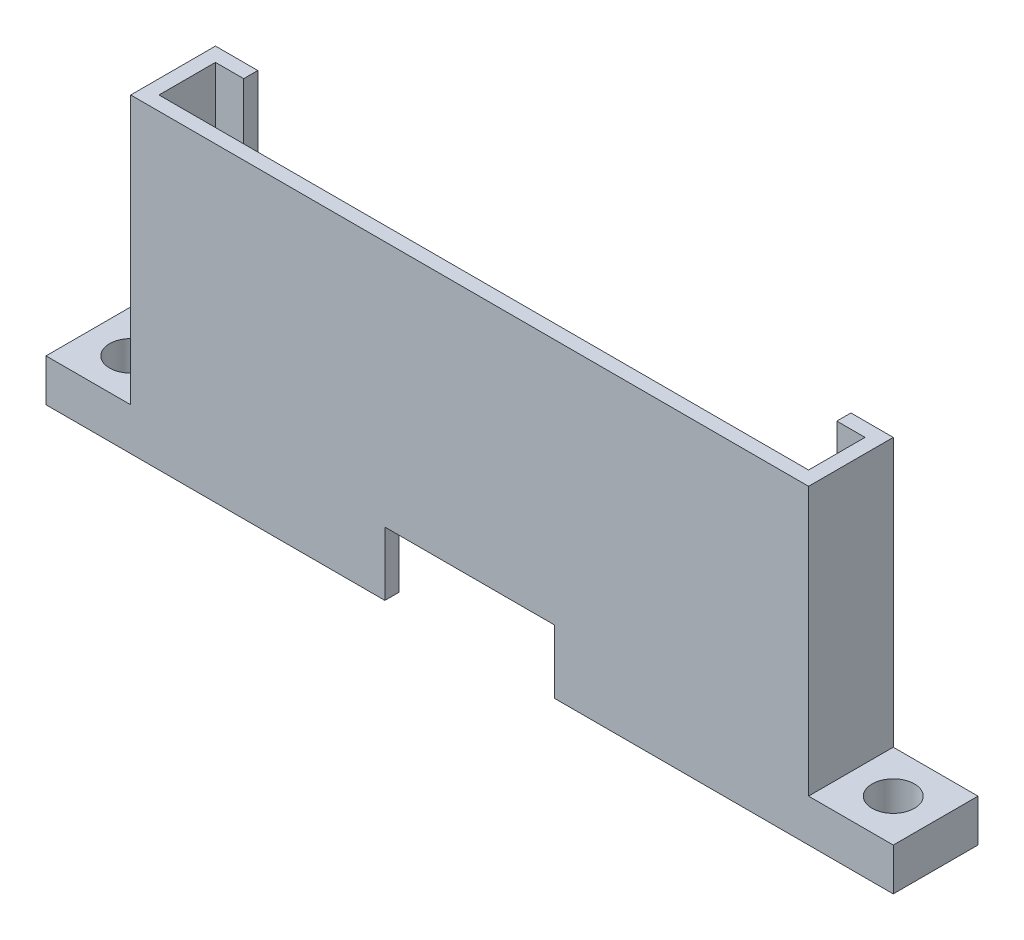
SolidWorks part; units mm, degrees
ref_plane "前基準面" through (0, 0, 0) normal (0, 0, 1) x (1, 0, 0)
ref_plane "上基準面" through (0, 0, 0) normal (0, 1, 0) x (1, 0, 0)
ref_plane "右基準面" through (0, 0, 0) normal (1, 0, 0) x (0, 0, -1)
sketch "草圖1" plane through (0, 0, 0) normal (0, 0, 1) x (1, 0, 0)
  line L1 (0, 0) -> (-48, 0)
  line L2 (0, 0) -> (0, -22)
  line L3 (0, -22) -> (-48, -22)
  line L4 (-48, 0) -> (-48, -22)
  point P6 (0, 0)
extrude "填料-伸長1" add sketch "草圖1" along normal blind 6
sketch "草圖4" plane through (0, 0, 0) normal (0, 1, 0) x (1, 0, 0)
  line L3 (-47, -5) -> (-1, -5)
  line L4 (-47, -5) -> (-47, -1)
  line L5 (-47, -1) -> (-1, -1)
  line L6 (-1, -5) -> (-1, -1)
extrude "除料-伸長2" cut sketch "草圖4" against normal blind 22
sketch "草圖5" plane through (0, 0, 0) normal (0, 1, 0) x (1, 0, 0)
  line L0 (-24, 0) -> (-24, -0.5)
  line L2 (0, 0) -> (-48, 0) construction
  line L3 (-1, -1) -> (-47, -1) construction
  line L4 (-45, 0) -> (-3, 0)
  line L5 (-45, 0) -> (-45, -1)
  line L6 (-45, -1) -> (-3, -1)
  line L7 (-3, 0) -> (-3, -1)
extrude "除料-伸長3" cut sketch "草圖5" against normal blind 22 contours L5 L4 L7 L6
sketch "草圖9" plane through (0, 0, 6) normal (0, 0, 1) x (1, 0, 0)
  line L1 (-48, -22) -> (0, -22) construction
  line L7 (-30, -17.5) -> (-18, -17.5)
  line L8 (-30, -17.5) -> (-30, -22)
  line L9 (-30, -22) -> (-18, -22)
  line L10 (-18, -17.5) -> (-18, -22)
extrude "除料-伸長5" cut sketch "草圖9" against normal blind 6 contours L8 L7 L10 L9
sketch "草圖10" plane through (0, 0, 0) normal (1, 0, 0) x (0, 0, -1)
  line L0 (0, -22) -> (0, 0) construction
  line L1 (-6, -22) -> (0, -22)
  line L2 (-6, -22) -> (-6, -19)
  line L3 (-6, -19) -> (0, -19)
  line L4 (0, -22) -> (0, -19)
extrude "填料-伸長2" add sketch "草圖10" along normal blind 6 contours L2 L1 L4 L3
sketch "草圖11" plane through (-48, 0, 0) normal (-1, 0, 0) x (0, 0, 1)
  line L0 (6, 0) -> (6, -22) construction
  line L1 (0, -22) -> (6, -22)
  line L2 (0, -22) -> (0, -19)
  line L3 (0, -19) -> (6, -19)
  line L4 (6, -22) -> (6, -19)
extrude "填料-伸長3" add sketch "草圖11" along normal blind 6 contours L2 L1 L4 L3
sketch "草圖12" plane through (0, -19, 0) normal (0, 1, 0) x (1, 0, 0)
  circle A0 centre (3, -3) radius 1.5
extrude "除料-伸長6" cut sketch "草圖12" against normal blind 3 contours A0
sketch "草圖14" plane through (0, -19, 0) normal (0, 1, 0) x (1, 0, 0)
  circle A0 centre (-51, -3) radius 1.5
extrude "除料-伸長7" cut sketch "草圖14" against normal blind 3 contours A0
